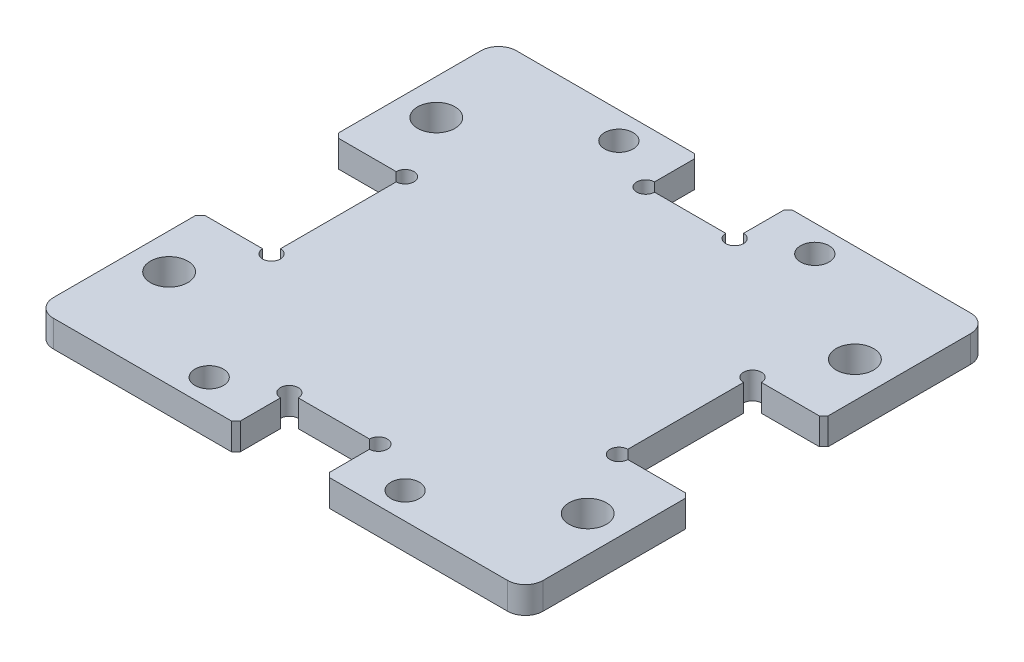
SolidWorks part; units mm, degrees
material "6061 合金"
ref_plane "前视基准面" through (0, 0, 0) normal (0, 0, 1) x (1, 0, 0)
ref_plane "上视基准面" through (0, 0, 0) normal (0, 1, 0) x (1, 0, 0)
ref_plane "右视基准面" through (0, 0, 0) normal (1, 0, 0) x (0, 0, -1)
sketch "草图1" plane through (0, 0, 0) normal (0, 1, 0) x (1, 0, 0)
  line L1 (-27.5, 26) -> (27.5, 26)
  line L2 (-27.5, 26) -> (-27.5, -26)
  line L3 (-27.5, -26) -> (27.5, -26)
  line L4 (27.5, 26) -> (27.5, -26)
  line L5 (-27.5, 26) -> (27.5, -26) construction
  line L6 (-27.5, -26) -> (27.5, 26) construction
  point P0 (0, 0)
  dimension "D1" = 52
  dimension "D2" = 55
extrude "凸台-拉伸1" add sketch "草图1" along normal blind 3
sketch "草图2" plane through (0, 3, 0) normal (0, 1, 0) x (1, 0, 0)
  line L0 (0, 8.4951) -> (0, -30.7559) construction
  line L1 (-5, -26) -> (-5, -20)
  line L2 (-27.5, -26) -> (27.5, -26) construction
  line L3 (-10.9458, 0) -> (11.3049, 0) construction
  line L4 (5, -26) -> (5, -20)
  line L5 (-5, -20) -> (5, -20)
  line L6 (-5, -26) -> (5, -26)
  line L7 (-5, 26) -> (5, 26)
  line L8 (-5, 20) -> (5, 20)
  line L9 (5, 26) -> (5, 20)
  line L10 (-5, 26) -> (-5, 20)
  dimension "D1" = 10
  dimension "D2" = 6
extrude "切除-拉伸1" cut sketch "草图2" against normal through all
sketch "草图3" plane through (0, 3, 0) normal (0, 1, 0) x (1, 0, 0)
  circle A0 centre (-5, 20) radius 1
  circle A1 centre (5, 20) radius 1
  circle A2 centre (-5, -20) radius 1
  circle A3 centre (5, -20) radius 1
  dimension "D1" = 2
  dimension "D2" = 2
  dimension "D3" = 2
  dimension "D4" = 2
extrude "切除-拉伸2" cut sketch "草图3" against normal through all
sketch "草图4" plane through (0, 3, 0) normal (0, 1, 0) x (1, 0, 0)
  line L0 (-15.6483, -23) -> (14.9993, -23) construction
  line L1 (5, -26) -> (27.5, -26) construction
  line L2 (0, -10.8532) -> (0, -37.4261) construction
  line L3 (-6.0796, 0) -> (6.8127, 0) construction
  circle A0 centre (-11, -23) radius 1.6
  circle A1 centre (11, -23) radius 1.6
  circle A2 centre (11, 23) radius 1.6
  circle A3 centre (-11, 23) radius 1.6
  dimension "D2" = 3.2
  dimension "D3" = 22
  dimension "D1" = 3
extrude "切除-拉伸3" cut sketch "草图4" against normal through all
chamfer "倒角1" distance 0.5 angle 45 4 edges at (5, 1.5, 26) (-5, 1.5, 26) (-5, 1.5, -26) (5, 1.5, -26)
sketch "草图5" plane through (0, 3, 0) normal (0, 1, 0) x (1, 0, 0)
  line L0 (-41.5366, 0) -> (45.647, 0) construction
  line L1 (-27.5, 7.5) -> (-19.5, 7.5)
  line L2 (-27.5, 26) -> (-27.5, -26) construction
  line L3 (-27.5, -7.5) -> (-19.5, -7.5)
  line L4 (-19.5, 7.5) -> (-19.5, -7.5)
  line L5 (-27.5, -7.5) -> (-27.5, 7.5)
  line L6 (0, 35.7728) -> (0, -43.1621) construction
  line L7 (27.5, -7.5) -> (27.5, 7.5)
  line L8 (19.5, 7.5) -> (19.5, -7.5)
  line L9 (27.5, -7.5) -> (19.5, -7.5)
  line L10 (27.5, 7.5) -> (19.5, 7.5)
  dimension "D1" = 15
  dimension "D2" = 8
extrude "切除-拉伸4" cut sketch "草图5" against normal through all
sketch "草图6" plane through (0, 3, 0) normal (0, 1, 0) x (1, 0, 0)
  circle A0 centre (19.5, 7.5) radius 1
  circle A1 centre (19.5, -7.5) radius 1
  circle A2 centre (-19.5, 7.5) radius 1
  circle A3 centre (-19.5, -7.5) radius 1
  dimension "D1" = 2
  dimension "D2" = 2
  dimension "D3" = 2
  dimension "D4" = 2
extrude "切除-拉伸5" cut sketch "草图6" against normal through all
sketch "草图7" plane through (0, 3, 0) normal (0, 1, 0) x (1, 0, 0)
  line L0 (0, 28.0877) -> (0, -26.7897) construction
  line L1 (-40.8155, 0) -> (-20.552, 0) construction
  line L2 (-27.5, 26) -> (-27.5, 7.5) construction
  circle A0 centre (-23.5, 15) radius 2.1
  circle A1 centre (-23.5, -15) radius 2.1
  circle A2 centre (23.5, -15) radius 2.1
  circle A3 centre (23.5, 15) radius 2.1
  dimension "D1" = 4.2
  dimension "D2" = 30
  dimension "D3" = 4
extrude "切除-拉伸6" cut sketch "草图7" against normal through all
chamfer "倒角2" distance 0.5 angle 45 4 edges at (27.5, 1.5, 7.5) (27.5, 1.5, -7.5) (-27.5, 1.5, 7.5) (-27.5, 1.5, -7.5)
fillet "圆角1" radius 2 4 edges at (-27.5, 1.5, 26) (-27.5, 1.5, -26) (27.5, 1.5, -26) (27.5, 1.5, 26)
